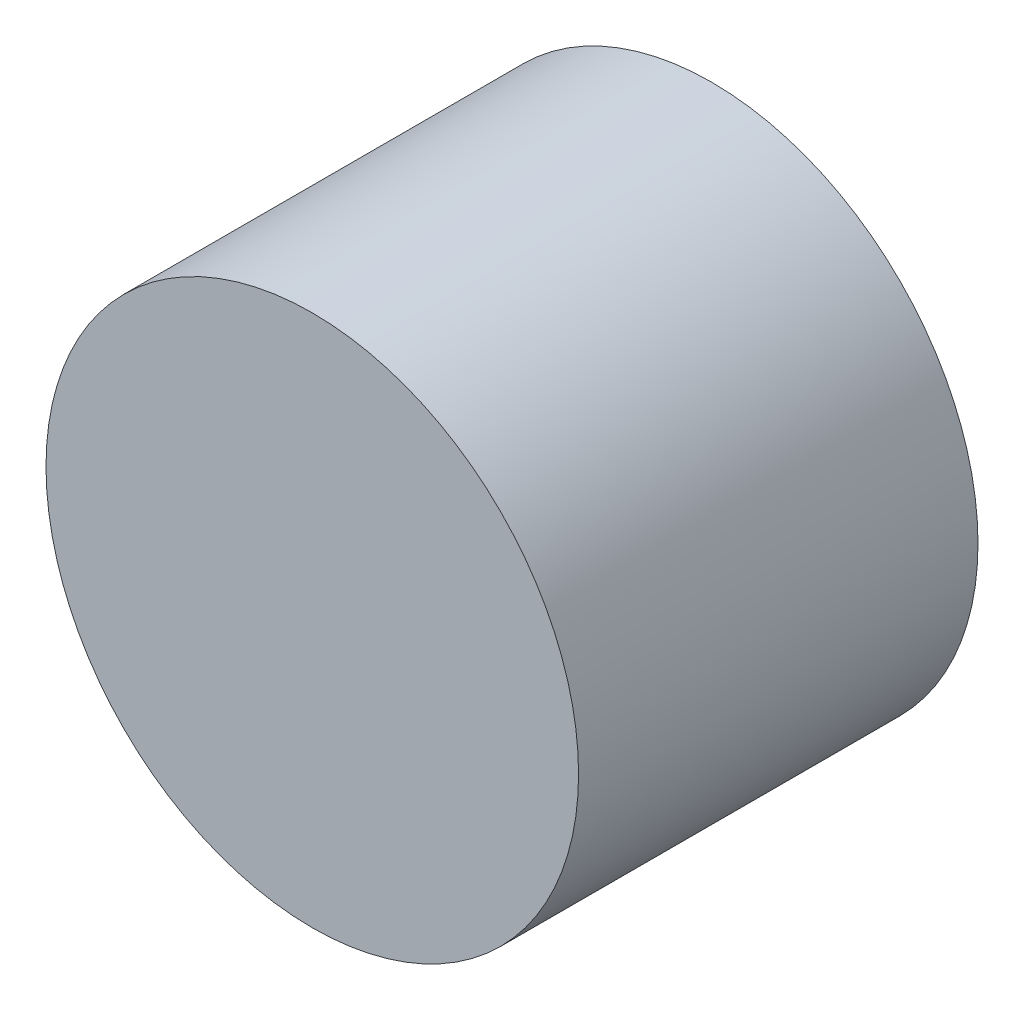
SolidWorks part; units mm, degrees
ref_plane "Front Plane" through (0, 0, 0) normal (0, 0, 1) x (1, 0, 0)
ref_plane "Top Plane" through (0, 0, 0) normal (0, 1, 0) x (1, 0, 0)
ref_plane "Right Plane" through (0, 0, 0) normal (1, 0, 0) x (0, 0, -1)
sketch "草圖1" plane through (0, 0, 0) normal (0, 0, 1) x (1, 0, 0)
  circle A0 centre (0, 0) radius 4
extrude "填料-伸長1" add sketch "草圖1" along normal blind 6
